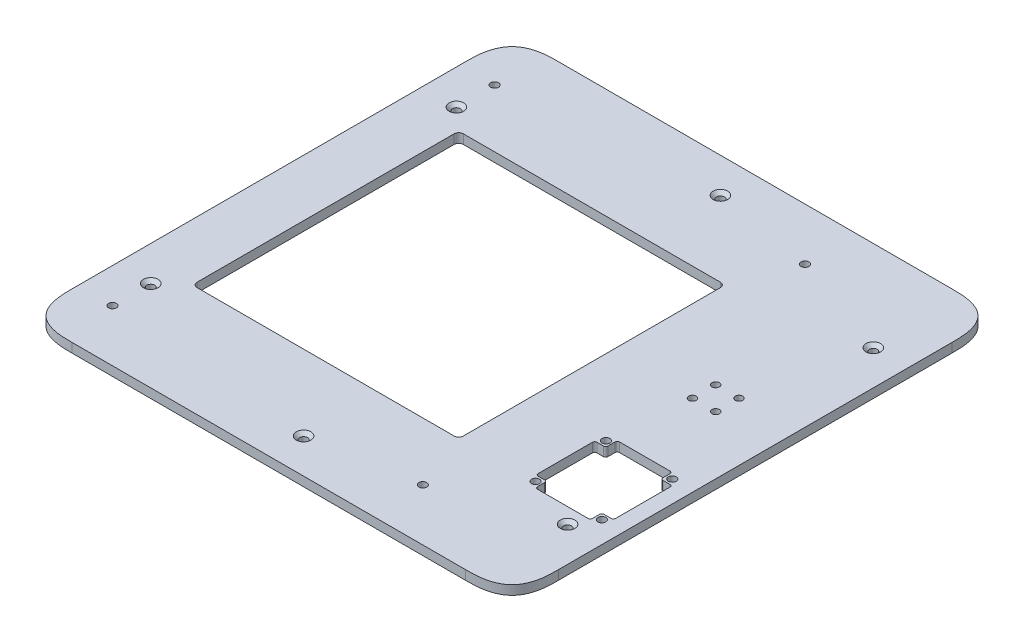
SolidWorks part; units mm, degrees
ref_plane "Спереди" through (0, 0, 0) normal (0, 0, 1) x (1, 0, 0)
ref_plane "Сверху" through (0, 0, 0) normal (0, 1, 0) x (1, 0, 0)
ref_plane "Справа" through (0, 0, 0) normal (1, 0, 0) x (0, 0, -1)
sketch "Эскиз1" plane through (0, 0, 0) normal (0, 1, 0) x (1, 0, 0)
  line L0 (105, -85) -> (105, 85) construction
  line L1 (-85, -105) -> (85, -105) construction
  line L2 (-105, -85) -> (-105, 85) construction
  line L3 (-85, 105) -> (85, 105) construction
  line L4 (105, -85) -> (105, 85)
  line L5 (-85, -105) -> (85, -105)
  line L6 (-105, -85) -> (-105, 85)
  line L7 (-85, 105) -> (85, 105)
  spline S0 degree 2 poles (87.7075, -914.8503) (105.4682, 60.1336) (104.9873, 87.0793) (104.9672, 88.2064) (104.906, 89.1526) (104.7612, 91.3925) (104.3447, 93.2636) (103.3156, 97.8875) (100.6213, 100.5918) (97.9211, 103.3021) (93.2885, 104.3392) (91.4177, 104.758) (89.1768, 104.9045) (88.2251, 104.9667) (87.0892, 104.9871) (60.1244, 105.4731) (-914.8432, 87.5821) knots -2.308504 -2.308504 -2.308504 0.0625 0.0625 0.125 0.125 0.25 0.25 0.5 0.5 0.75 0.75 0.875 0.875 0.9375 0.9375 3.300825 3.300825 3.300825 only from (105, 85) to (85, 105) construction
  spline S1 degree 2 poles (-914.8503, -87.7075) (60.1336, -105.4682) (87.0793, -104.9873) (88.2064, -104.9672) (89.1526, -104.906) (91.3925, -104.7612) (93.2636, -104.3447) (97.8875, -103.3156) (100.5918, -100.6213) (103.3021, -97.9211) (104.3392, -93.2885) (104.758, -91.4177) (104.9045, -89.1768) (104.9667, -88.2251) (104.9871, -87.0892) (105.4731, -60.1244) (87.5821, 914.8432) knots -2.308504 -2.308504 -2.308504 0.0625 0.0625 0.125 0.125 0.25 0.25 0.5 0.5 0.75 0.75 0.875 0.875 0.9375 0.9375 3.300825 3.300825 3.300825 only from (85, -105) to (105, -85) construction
  spline S2 degree 2 poles (-87.7075, 914.8503) (-105.4682, -60.1336) (-104.9873, -87.0793) (-104.9672, -88.2064) (-104.906, -89.1526) (-104.7612, -91.3925) (-104.3447, -93.2636) (-103.3156, -97.8875) (-100.6213, -100.5918) (-97.9211, -103.3021) (-93.2885, -104.3392) (-91.4177, -104.758) (-89.1768, -104.9045) (-88.2251, -104.9667) (-87.0892, -104.9871) (-60.1244, -105.4731) (914.8432, -87.5821) knots -2.308504 -2.308504 -2.308504 0.0625 0.0625 0.125 0.125 0.25 0.25 0.5 0.5 0.75 0.75 0.875 0.875 0.9375 0.9375 3.300825 3.300825 3.300825 only from (-105, -85) to (-85, -105) construction
  spline S3 degree 2 poles (914.8503, 87.7075) (-60.1336, 105.4682) (-87.0793, 104.9873) (-88.2064, 104.9672) (-89.1526, 104.906) (-91.3925, 104.7612) (-93.2636, 104.3447) (-97.8875, 103.3156) (-100.5918, 100.6213) (-103.3021, 97.9211) (-104.3392, 93.2885) (-104.758, 91.4177) (-104.9045, 89.1768) (-104.9667, 88.2251) (-104.9871, 87.0892) (-105.4731, 60.1244) (-87.5821, -914.8432) knots -2.308504 -2.308504 -2.308504 0.0625 0.0625 0.125 0.125 0.25 0.25 0.5 0.5 0.75 0.75 0.875 0.875 0.9375 0.9375 3.300825 3.300825 3.300825 only from (-85, 105) to (-105, 85) construction
  spline S4 degree 2 poles (105, 85) (105, 86.369) (104.9873, 87.0793) (104.9672, 88.2064) (104.906, 89.1526) (104.7612, 91.3925) (104.3447, 93.2636) (103.3156, 97.8875) (100.6213, 100.5918) (97.9211, 103.3021) (93.2885, 104.3392) (91.4177, 104.758) (89.1768, 104.9045) (88.2251, 104.9667) (87.0892, 104.9871) (86.3761, 105) (85, 105) knots 0 0 0 0.0625 0.0625 0.125 0.125 0.25 0.25 0.5 0.5 0.75 0.75 0.875 0.875 0.9375 0.9375 1 1 1
  spline S5 degree 2 poles (85, -105) (86.369, -105) (87.0793, -104.9873) (88.2064, -104.9672) (89.1526, -104.906) (91.3925, -104.7612) (93.2636, -104.3447) (97.8875, -103.3156) (100.5918, -100.6213) (103.3021, -97.9211) (104.3392, -93.2885) (104.758, -91.4177) (104.9045, -89.1768) (104.9667, -88.2251) (104.9871, -87.0892) (105, -86.3761) (105, -85) knots 0 0 0 0.0625 0.0625 0.125 0.125 0.25 0.25 0.5 0.5 0.75 0.75 0.875 0.875 0.9375 0.9375 1 1 1
  spline S6 degree 2 poles (-105, -85) (-105, -86.369) (-104.9873, -87.0793) (-104.9672, -88.2064) (-104.906, -89.1526) (-104.7612, -91.3925) (-104.3447, -93.2636) (-103.3156, -97.8875) (-100.6213, -100.5918) (-97.9211, -103.3021) (-93.2885, -104.3392) (-91.4177, -104.758) (-89.1768, -104.9045) (-88.2251, -104.9667) (-87.0892, -104.9871) (-86.3761, -105) (-85, -105) knots 0 0 0 0.0625 0.0625 0.125 0.125 0.25 0.25 0.5 0.5 0.75 0.75 0.875 0.875 0.9375 0.9375 1 1 1
  spline S7 degree 2 poles (-85, 105) (-86.369, 105) (-87.0793, 104.9873) (-88.2064, 104.9672) (-89.1526, 104.906) (-91.3925, 104.7612) (-93.2636, 104.3447) (-97.8875, 103.3156) (-100.5918, 100.6213) (-103.3021, 97.9211) (-104.3392, 93.2885) (-104.758, 91.4177) (-104.9045, 89.1768) (-104.9667, 88.2251) (-104.9871, 87.0892) (-105, 86.3761) (-105, 85) knots 0 0 0 0.0625 0.0625 0.125 0.125 0.25 0.25 0.5 0.5 0.75 0.75 0.875 0.875 0.9375 0.9375 1 1 1
extrude "Бобышка-Вытянуть1" add sketch "Эскиз1" along normal blind 4
hole_wizard "Зенковка для винта с полупотайной головкой M32" positions "Эскиз10" profile "Эскиз11" countersink size "M3" standard "DIN" end condition through all
sketch "Эскиз10" plane through (0, 4, 0) normal (0, 1, 0) x (1, 0, 0)
  point P0 (90, -66)
  point P6 (0, -90)
  point P11 (-90, -66)
  point P19 (0, 90)
  point P22 (-90, 66)
  point P25 (90, 66)
sketch "Эскиз11" plane through (90, 4, 66) normal (1, 0, 0) x (0, 0, 1)
  line L0 (0, 0) -> (0, 4.05)
  line L1 (0, 4.05) -> (1.7, 4.05)
  line L2 (1.7, 4.05) -> (1.7, 1.45)
  line L3 (1.7, 1.45) -> (3.15, 0)
  line L5 (3.15, 0) -> (0, 0)
  line L6 (-1.7, 1.45) -> (-3.15, 0) construction
  line L11 (0, -6.35) -> (0, 107.95) construction
  dimension "Диаметр сквозного отверстия" = 3.4
  dimension "Глубина сквозного отверстия" = 4.05
  dimension "Диаметр передней зенковки" = 6.3
  dimension "Угол передней зенковки" = 90
hole_wizard "Зенковка для винта с полупотайной головкой M33" positions "Эскиз13" profile "Эскиз14" countersink size "M3" standard "DIN"
sketch "Эскиз13" plane through (0, 0, 0) normal (0, -1, 0) x (-1, 0, 0)
  circle A0 centre (-69.8295, 8.0795) radius 1.75 construction
  circle A1 centre (-79.8705, 8.0795) radius 1.75 construction
  circle A2 centre (-79.8705, 18.1205) radius 1.75 construction
  circle A3 centre (-69.8295, 18.1205) radius 1.75 construction
  circle A4 centre (-69.8295, 8.0795) radius 1.75 construction
  circle A5 centre (-79.8705, 8.0795) radius 1.75 construction
  circle A6 centre (-79.8705, 18.1205) radius 1.75 construction
  circle A7 centre (-69.8295, 18.1205) radius 1.75 construction
  point P1 (-69.8295, 8.0795)
  point P3 (-79.8705, 8.0795)
  point P5 (-79.8705, 18.1205)
  point P7 (-69.8295, 18.1205)
sketch "Эскиз14" plane through (69.8295, 0, -8.0795) normal (1, 0, 0) x (0, 0, -1)
  line L0 (0, 0) -> (0, 4.9614)
  line L1 (0, 4.9614) -> (1.6, 4)
  line L2 (1.6, 4) -> (1.6, 1.55)
  line L3 (1.6, 1.55) -> (3.15, 0)
  line L5 (3.15, 0) -> (0, 0)
  line L6 (-1.6, 1.55) -> (-3.15, 0) construction
  line L10 (0, 4.9614) -> (-1.6, 4) construction
  line L11 (0, -6.35) -> (0, 107.95) construction
  dimension "Диаметр отверстия" = 3.2
  dimension "Глубина отверстия" = 4
  dimension "Диаметр передней зенковки" = 6.3
  dimension "Угол передней зенковки" = 90
  dimension "Угол заточки сверла" = 118
hole_wizard "Зенковка для винта с полупотайной головкой M34" positions "Эскиз15" profile "Эскиз17" countersink size "M3" standard "DIN" end condition through all
sketch "Эскиз15" plane through (0, 0, 0) normal (0, -1, 0) x (-1, 0, 0)
  point P0 (90, 82.5)
  point P3 (-44, 82.5)
  point P6 (-44, -82.5)
  point P9 (90, -82.5)
sketch "Эскиз17" plane through (-90, 0, -82.5) normal (1, 0, 0) x (0, 0, -1)
  line L0 (0, 0) -> (0, 4.05)
  line L1 (0, 4.05) -> (1.7, 4.05)
  line L2 (1.7, 4.05) -> (1.7, 1.45)
  line L3 (1.7, 1.45) -> (3.15, 0)
  line L5 (3.15, 0) -> (0, 0)
  line L6 (-1.7, 1.45) -> (-3.15, 0) construction
  line L11 (0, -6.35) -> (0, 107.95) construction
  dimension "Диаметр сквозного отверстия" = 3.4
  dimension "Глубина сквозного отверстия" = 4.05
  dimension "Диаметр передней зенковки" = 6.3
  dimension "Угол передней зенковки" = 90
sketch "Эскиз18" plane through (0, 4, 0) normal (0, 1, 0) x (1, 0, 0)
  line L0 (98.2, -24) -> (64.7, -24) construction
  line L1 (98.2, -59.4) -> (98.2, -24) construction
  line L2 (64.7, -59.4) -> (98.2, -59.4) construction
  line L3 (98.2, -24) -> (64.7, -24) construction
  line L4 (98.2, -59.4) -> (98.2, -24) construction
  line L5 (64.7, -59.4) -> (98.2, -59.4) construction
  line L6 (64.7, -54.4) -> (64.7, -29)
  line L7 (93.2, -29) -> (98.2, -29)
  line L8 (93.2, -29) -> (93.2, -24)
  line L9 (93.2, -24) -> (98.2, -24) construction
  line L10 (98.2, -29) -> (98.2, -24) construction
  line L11 (93.2, -29) -> (98.2, -24) construction
  line L12 (93.2, -24) -> (98.2, -29) construction
  line L13 (98.2, -59.4) -> (93.2, -59.4) construction
  line L14 (98.2, -59.4) -> (98.2, -54.4) construction
  line L15 (98.2, -54.4) -> (93.2, -54.4)
  line L16 (93.2, -59.4) -> (93.2, -54.4)
  line L17 (98.2, -59.4) -> (93.2, -54.4) construction
  line L18 (98.2, -54.4) -> (93.2, -59.4) construction
  line L19 (69.4481, -29) -> (64.7, -29)
  line L20 (69.4481, -29) -> (69.4481, -24)
  line L21 (69.4481, -24) -> (64.7, -24) construction
  line L22 (64.7, -29) -> (64.7, -24) construction
  line L23 (69.4481, -29) -> (64.7, -24) construction
  line L24 (69.4481, -24) -> (64.7, -29) construction
  line L25 (69.4481, -54.4) -> (64.7, -54.4)
  line L26 (69.4481, -54.4) -> (69.4481, -59.4)
  line L27 (69.4481, -59.4) -> (64.7, -59.4) construction
  line L28 (64.7, -54.4) -> (64.7, -59.4) construction
  line L29 (69.4481, -54.4) -> (64.7, -59.4) construction
  line L30 (69.4481, -59.4) -> (64.7, -54.4) construction
  line L31 (93.2, -24) -> (69.4481, -24)
  line L32 (98.2, -29) -> (98.2, -54.4)
  line L33 (69.4481, -59.4) -> (93.2, -59.4)
  circle A0 centre (67.074, -26.5) radius 1.5 construction
  circle A1 centre (67.074, -56.9) radius 1.5 construction
  circle A2 centre (95.7, -56.9) radius 1.5 construction
  circle A3 centre (67.074, -26.5) radius 1.5 construction
  circle A4 centre (67.074, -56.9) radius 1.5 construction
  circle A5 centre (95.7, -56.9) radius 1.5 construction
  circle A6 centre (95.7, -26.5) radius 1.5 construction
  circle A7 centre (95.7, -26.5) radius 1.5 construction
  point P16 (95.7, -26.5)
  point P22 (95.7, -56.9)
extrude "Вырез-Вытянуть1" cut sketch "Эскиз18" against normal through all
fillet "Скругление2" radius 1 12 edges at (64.7, 2, 54.4) (69.4481, 2, 54.4) (69.4481, 2, 59.4) (93.2, 2, 59.4) (93.2, 2, 54.4) (98.2, 2, 54.4) (98.2, 2, 29) (93.2, 2, 29) (93.2, 2, 24) (69.4481, 2, 24) (69.4481, 2, 29) (64.7, 2, 29)
hole_wizard "Отверстие с зазором M31" positions "Эскиз21" profile "Эскиз23" hole size "M3" standard "DIN" end condition through all
sketch "Эскиз21" plane through (0, 4, 0) normal (0, 1, 0) x (1, 0, 0)
  point P0 (95.7, -56.9)
  point P3 (67.074, -56.9)
  point P6 (67.074, -26.5)
  point P9 (95.7, -26.5)
sketch "Эскиз23" plane through (95.7, 4, 56.9) normal (1, 0, 0) x (0, 0, 1)
  line L0 (0, 0) -> (0, 4.05)
  line L1 (0, 4.05) -> (1.7, 4.05)
  line L2 (1.7, 4.05) -> (1.7, 0)
  line L5 (1.7, 0) -> (0, 0)
  line L11 (0, -6.35) -> (0, 107.95) construction
  dimension "Диаметр сквозного отверстия" = 3.4
  dimension "Глубина сквозного отверстия" = 4.05
hole_wizard "Отверстие с зазором M32" positions "Эскиз26" profile "Эскиз27" hole size "M3" standard "DIN" end condition through all
sketch "Эскиз26" plane through (0, 4, 0) normal (0, 1, 0) x (1, 0, 0)
  point P0 (67.074, -56.9)
  point P3 (95.7, -56.9)
  point P9 (95.7, -26.5)
  point P12 (67.074, -26.5)
sketch "Эскиз27" plane through (67.074, 4, 56.9) normal (1, 0, 0) x (0, 0, 1)
  line L0 (0, 0) -> (0, 4.05)
  line L1 (0, 4.05) -> (1.7, 4.05)
  line L2 (1.7, 4.05) -> (1.7, 0)
  line L5 (1.7, 0) -> (0, 0)
  line L11 (0, -6.35) -> (0, 107.95) construction
  dimension "Диаметр сквозного отверстия" = 3.4
  dimension "Глубина сквозного отверстия" = 4.05
sketch "Эскиз28" plane through (0, 4, 0) normal (0, 1, 0) x (1, 0, 0)
  line L0 (-78.5, -57.5) -> (32.5, -57.5) construction
  line L1 (34.5, -55.5) -> (34.5, 55.5) construction
  line L2 (-80.5, 55.5) -> (-80.5, -55.5) construction
  line L3 (32.5, 57.5) -> (-78.5, 57.5) construction
  line L4 (-78.5, -57.5) -> (32.5, -57.5)
  line L5 (34.5, -55.5) -> (34.5, 55.5)
  line L6 (-80.5, 55.5) -> (-80.5, -55.5)
  line L7 (32.5, 57.5) -> (-78.5, 57.5)
  arc A0 (-80.5, -55.5) -> (-78.5, -57.5) centre (-78.5, -55.5) ccw construction
  arc A1 (32.5, -57.5) -> (34.5, -55.5) centre (32.5, -55.5) ccw construction
  arc A2 (34.5, 55.5) -> (32.5, 57.5) centre (32.5, 55.5) ccw construction
  arc A3 (-78.5, 57.5) -> (-80.5, 55.5) centre (-78.5, 55.5) ccw construction
  arc A4 (-80.5, -55.5) -> (-78.5, -57.5) centre (-78.5, -55.5) ccw
  arc A5 (32.5, -57.5) -> (34.5, -55.5) centre (32.5, -55.5) ccw
  arc A6 (34.5, 55.5) -> (32.5, 57.5) centre (32.5, 55.5) ccw
  arc A7 (-78.5, 57.5) -> (-80.5, 55.5) centre (-78.5, 55.5) ccw
extrude "Вырез-Вытянуть2" cut sketch "Эскиз28" against normal through all
